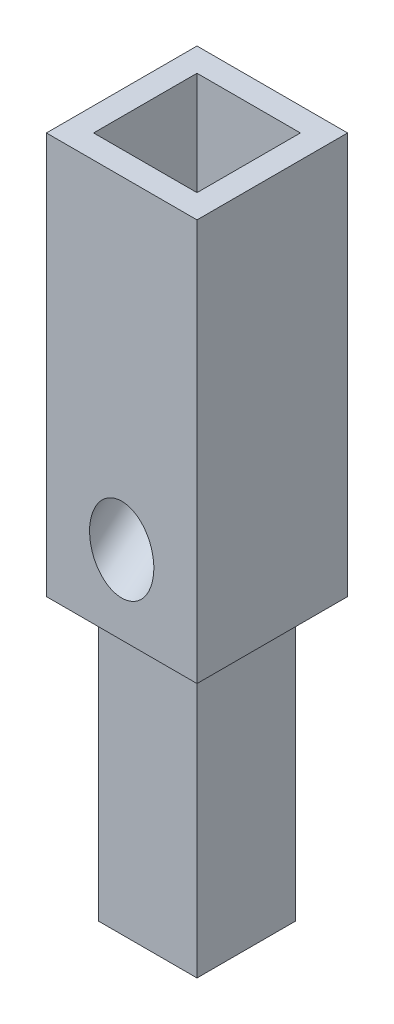
SolidWorks part; units mm, degrees
ref_plane "Спереди" through (0, 0, 0) normal (0, 0, 1) x (1, 0, 0)
ref_plane "Сверху" through (0, 0, 0) normal (0, 1, 0) x (1, 0, 0)
ref_plane "Справа" through (0, 0, 0) normal (1, 0, 0) x (0, 0, -1)
sketch "Sketch1" plane through (0, 0, 0) normal (0, 1, 0) x (1, 0, 0)
  line L1 (7.5, -7.5) -> (-7.5, -7.5)
  line L2 (7.5, -7.5) -> (7.5, 7.5)
  line L3 (7.5, 7.5) -> (-7.5, 7.5)
  line L4 (-7.5, -7.5) -> (-7.5, 7.5)
  line L5 (7.5, -7.5) -> (-7.5, 7.5) construction
  line L6 (7.5, 7.5) -> (-7.5, -7.5) construction
  point P0 (0, 0)
  dimension "D1" = 15
extrude "Boss-Extrude1" add sketch "Sketch1" along normal blind 40
sketch "Sketch2" plane through (0, 0, 0) normal (0, -1, 0) x (1, 0, 0)
  line L1 (-4.9, 4.9) -> (4.9, 4.9)
  line L2 (-4.9, 4.9) -> (-4.9, -4.9)
  line L3 (-4.9, -4.9) -> (4.9, -4.9)
  line L4 (4.9, 4.9) -> (4.9, -4.9)
  line L5 (-4.9, 4.9) -> (4.9, -4.9) construction
  line L6 (-4.9, -4.9) -> (4.9, 4.9) construction
  point P0 (0, 0)
  dimension "D1" = 9.8
extrude "Boss-Extrude2" add sketch "Sketch2" along normal blind 28
sketch "Sketch3" plane through (0, -28, 0) normal (0, -1, 0) x (1, 0, 0)
  line L0 (4.9, -4.9) -> (-4.9, 4.9) construction
  circle A0 centre (0, 0) radius 1.5
  dimension "D1" = 3
extrude "Cut-Extrude1" cut sketch "Sketch3" against normal through all
sketch "Sketch4" plane through (0, -28, 0) normal (0, -1, 0) x (1, 0, 0)
  circle A0 centre (0, 0) radius 3.5
  dimension "D1" = 7
extrude "Cut-Extrude2" cut sketch "Sketch4" against normal blind 6
sketch "Sketch5" plane through (0, 40, 0) normal (0, 1, 0) x (1, 0, 0)
  line L0 (-7.5, 7.5) -> (7.5, -7.5) construction
  line L2 (5.15, -5.15) -> (-5.15, -5.15)
  line L3 (5.15, -5.15) -> (5.15, 5.15)
  line L4 (5.15, 5.15) -> (-5.15, 5.15)
  line L5 (-5.15, -5.15) -> (-5.15, 5.15)
  line L6 (5.15, -5.15) -> (-5.15, 5.15) construction
  line L7 (5.15, 5.15) -> (-5.15, -5.15) construction
  point P4 (0, 0)
  dimension "D1" = 10.3
extrude "Cut-Extrude3" cut sketch "Sketch5" against normal blind 25
sketch "Sketch6" plane through (5.15, 0, 0) normal (-1, 0, 0) x (0, 0, 1)
  line L0 (5.15, 15) -> (-4.95, 2.9633)
  line L1 (-4.95, 2.9633) -> (-4.95, 15)
  line L2 (-4.95, 15) -> (5.15, 15)
  line L4 (5.15, 40) -> (-5.15, 40) construction
  line L5 (5.15, 15) -> (5.15, 40) construction
  dimension "D1" = 10.1
  dimension "D2" = 50
  dimension "D3" = 25
extrude "Cut-Extrude8" cut sketch "Sketch6" along normal up to surface (10.3 mm away) up to face at (-5.15, 27.5, 0)
sketch "Sketch8" plane through (0, 3.6618, -4.3639) normal (0, 0.6428, -0.766) x (-1, 0, 0)
  line L0 (-5.15, 10.801) -> (5.15, 10.801) construction
  line L1 (-5.15, -0.9118) -> (-5.15, 14.801) construction
  line L2 (5.15, -0.9118) -> (5.15, 14.801) construction
  line L3 (5.15, 14.801) -> (-5.15, 14.801) construction
  circle A0 centre (0, 10.801) radius 3.2
  point P9 (0, 10.801)
  dimension "D1" = 6.4
  dimension "D2" = 4
extrude "Cut-Extrude10" cut sketch "Sketch8" against normal through all
